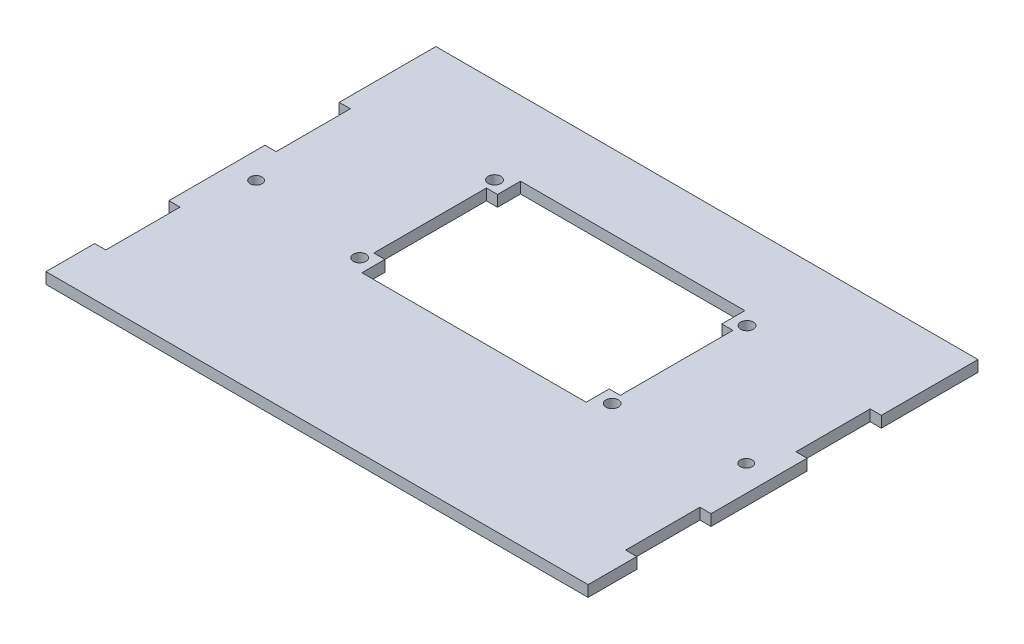
SolidWorks part; units mm, degrees
ref_plane "Front Plane" through (0, 0, 0) normal (0, 0, 1) x (1, 0, 0)
ref_plane "Top Plane" through (0, 0, 0) normal (0, 1, 0) x (1, 0, 0)
ref_plane "Right Plane" through (0, 0, 0) normal (1, 0, 0) x (0, 0, -1)
other "Configuration Table"
sketch "Sketch1" plane through (0, 0, 0) normal (0, 1, 0) x (1, 0, 0)
  line L1 (73, -52.5) -> (-73, -52.5)
  line L2 (73, -52.5) -> (73, 52.5)
  line L3 (73, 52.5) -> (-73, 52.5)
  line L4 (-73, -52.5) -> (-73, 52.5)
  line L5 (73, -52.5) -> (-73, 52.5) construction
  line L6 (73, 52.5) -> (-73, -52.5) construction
  point P0 (0, 0)
  dimension "D1" = 146
  dimension "D2" = 105
extrude "Boss-Extrude1" add sketch "Sketch1" along normal blind 3
sketch "Sketch2" plane through (0, 3, 0) normal (0, 1, 0) x (1, 0, 0)
  line L9 (73, -52.5) -> (73, 52.5) construction
  line L14 (-70, 26.47) -> (-70, 6.47)
  line L42 (-70, 26.47) -> (-73, 26.47)
  line L43 (-73, 52.5) -> (-73, -52.5) construction
  line L44 (-73, 26.47) -> (-73, 6.47)
  line L45 (-73, 6.47) -> (-70, 6.47)
  line L46 (70, 6.47) -> (70, 26.47)
  line L47 (70, 26.47) -> (73, 26.47)
  line L48 (73, 26.47) -> (73, 6.47)
  line L49 (73, 6.47) -> (70, 6.47)
  line L54 (-70, -39.4) -> (-70, -19.4)
  line L55 (-70, -19.4) -> (-73, -19.4)
  line L56 (-73, -19.4) -> (-73, -39.4)
  line L57 (-73, -39.4) -> (-70, -39.4)
  line L67 (70, -39.4) -> (70, -19.4)
  line L68 (70, -19.4) -> (73, -19.4)
  line L69 (73, -19.4) -> (73, -39.4)
  line L70 (73, -39.4) -> (70, -39.4)
  dimension "D2" = 13.1
  dimension "D9" = 20
  dimension "D11" = 3
  dimension "D12" = 25.87
  dimension "D13" = 20
extrude "Cut-Extrude1" cut sketch "Sketch2" against normal blind 10
sketch "Sketch3" plane through (0, 0, 0) normal (0, -1, 0) x (-1, 0, 0)
  line L0 (0, 52.5) -> (0, -52.5) construction
  line L1 (-34, 29.3) -> (-34, 32.5) construction
  line L2 (34, 29.3) -> (34, 32.5) construction
  line L3 (-73, 52.5) -> (73, 52.5) construction
  line L4 (73, -52.5) -> (-73, -52.5) construction
  line L6 (-37.2, 32.5) -> (-37.2, -10.22) construction
  line L7 (-37.2, -10.22) -> (37.2, -10.22) construction
  line L8 (37.2, -10.22) -> (37.2, 32.5) construction
  line L9 (37.2, 32.5) -> (-37.2, 32.5) construction
  line L10 (-37.2, -7.02) -> (-34, -7.02) construction
  line L11 (-37.2, 29.3) -> (-34, 29.3) construction
  line L12 (37.2, 29.3) -> (34, 29.3) construction
  line L13 (37.2, -7.02) -> (34, -7.02) construction
  line L14 (-34, -7.02) -> (-34, -10.22) construction
  line L15 (34, -7.02) -> (34, -10.22) construction
  line L16 (-30.2, 32.5) -> (-30.2, -10.22)
  line L17 (-30.2, -10.22) -> (30.2, -10.22)
  line L18 (30.2, -10.22) -> (30.2, 32.5)
  line L19 (30.2, 32.5) -> (-30.2, 32.5)
  line L20 (-30.2, 32.5) -> (30.2, -10.22) construction
  line L21 (30.2, 32.5) -> (-30.2, -10.22) construction
  circle A0 centre (-34, 29.3) radius 1.7
  circle A1 centre (-34, -7.02) radius 1.7
  circle A2 centre (34, 29.3) radius 1.7
  circle A3 centre (34, -7.02) radius 1.7
  point P6 (0, 0)
  point P29 (0, 11.14)
  dimension "D4" = 36.32
  dimension "D6" = 7
  dimension "D7" = 20
  dimension "D1" = 42.72
  dimension "D2" = 74.4
  dimension "D3" = 68
  dimension "D5" = 7
extrude "Cut-Extrude2" cut sketch "Sketch3" against normal blind 3
sketch "Sketch5" plane through (0, 0, 0) normal (0, -1, 0) x (-1, 0, 0)
  line L0 (30.2, -4.02) -> (33.2, -4.02)
  line L1 (30.2, -10.22) -> (30.2, 32.5) construction
  line L2 (33.2, -4.02) -> (33.2, 26.3)
  line L3 (33.2, 26.3) -> (30.2, 26.3)
  line L4 (30.2, 26.3) -> (30.2, -4.02)
  line L5 (-30.2, -4.02) -> (-33.2, -4.02)
  line L6 (-30.2, 32.5) -> (-30.2, -10.22) construction
  line L7 (-33.2, -4.02) -> (-33.2, 26.3)
  line L8 (-33.2, 26.3) -> (-30.2, 26.3)
  line L9 (-30.2, 26.3) -> (-30.2, -4.02)
  circle A0 centre (34, -7.02) radius 1.7 construction
  circle A1 centre (34, 29.3) radius 1.7 construction
  point P8 (31.7, -4.02)
  dimension "D1" = 3
  dimension "D2" = 3
  dimension "D3" = 3
  dimension "D4" = 3
extrude "Cut-Extrude4" cut sketch "Sketch5" against normal through all
sketch "Sketch6" plane through (0, 0, 0) normal (0, -1, 0) x (1, 0, 0)
  line L0 (-73, 52.5) -> (73, 52.5) construction
  line L1 (73, 19.4) -> (73, -6.47) construction
  circle A0 centre (-66, 2.92) radius 1.6
  circle A1 centre (66, 2.92) radius 1.6
  point P6 (0, 0)
  dimension "D2" = 7
  dimension "D1" = 49.58
  dimension "D3" = 7
extrude "Cut-Extrude5" cut sketch "Sketch6" against normal blind 10
